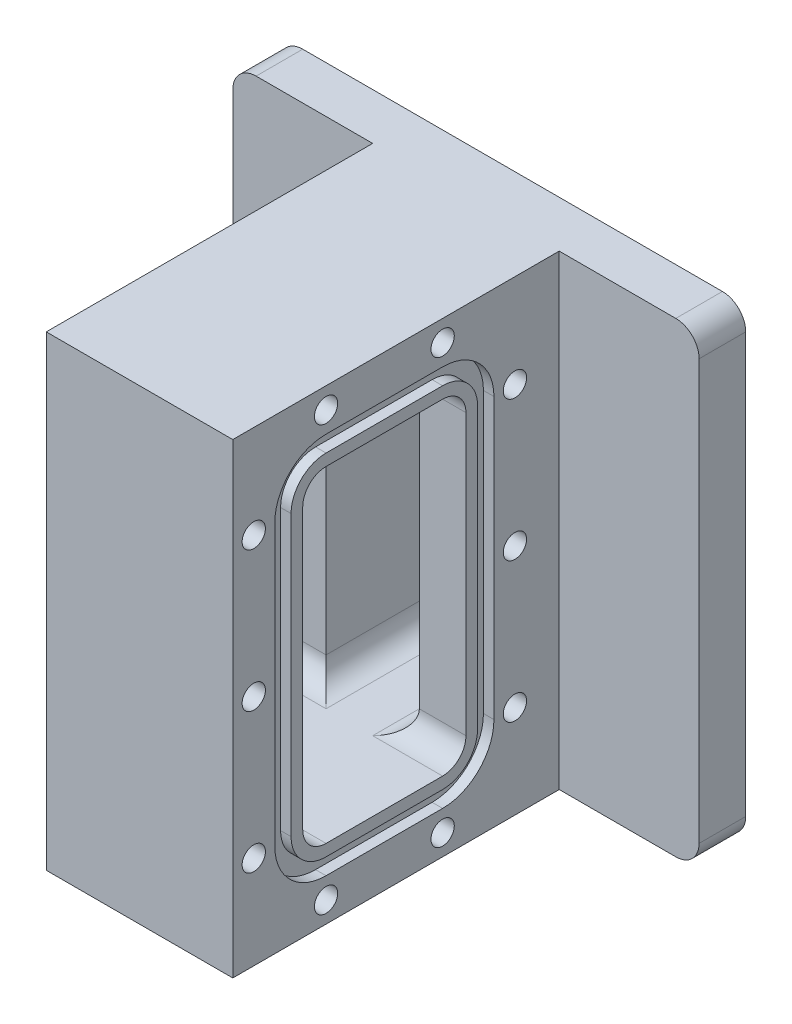
SolidWorks part; units mm, degrees
ref_plane "Front Plane" through (0, 0, 0) normal (0, 0, 1) x (1, 0, 0)
ref_plane "Top Plane" through (0, 0, 0) normal (0, 1, 0) x (1, 0, 0)
ref_plane "Right Plane" through (0, 0, 0) normal (1, 0, 0) x (0, 0, -1)
ref_plane "Plane1" through (99.9998, 0, 0) normal (1, 0, 0) x (0, 0, -1)
sketch "Sketch1" plane through (99.9998, 0, 0) normal (1, 0, 0) x (0, 0, -1)
  line L0 (0, 90.9998) -> (-79.9998, 90.9998)
  line L1 (-79.9998, 90.9998) -> (-79.9998, 0)
  line L2 (-79.9998, 0) -> (0, 0)
  line L3 (0, 0) -> (0, 90.9998)
extrude "Boss-Extrude1" add sketch "Sketch1" against normal blind 67.7499
sketch "Sketch2" plane through (32.2499, 0, 0) normal (-1, 0, 0) x (0, 0, 1)
  line L0 (0, 90.9998) -> (24, 90.9998)
  line L1 (24, 90.9998) -> (24, 9)
  line L2 (24, 9) -> (70.9999, 9)
  line L3 (70.9999, 9) -> (70.9999, 90.9998)
  line L4 (70.9999, 90.9998) -> (79.9998, 90.9998)
  line L5 (79.9998, 90.9998) -> (79.9998, 0)
  line L6 (79.9998, 0) -> (0, 0)
  line L7 (0, 0) -> (0, 90.9998)
extrude "Boss-Extrude2" add sketch "Sketch2" along normal blind 32.2499
sketch "Sketch3" plane through (0, 0, 0) normal (-1, 0, 0) x (0, 0, 1)
  line L0 (70.9999, 9) -> (24, 9)
  line L1 (24, 9) -> (24, 0)
  line L2 (24, 0) -> (79.9998, 0)
  line L3 (79.9998, 0) -> (79.9998, 90.9998)
  line L4 (79.9998, 90.9998) -> (70.9999, 90.9998)
  line L5 (70.9999, 90.9998) -> (70.9999, 9)
extrude "Cut-Extrude1" cut sketch "Sketch3" against normal blind 29.9999
sketch "Sketch4" plane through (0, 0, 24) normal (0, 0, 1) x (1, 0, 0)
  line L0 (29.9999, 0) -> (29.9999, 90.9998)
  line L1 (29.9999, 90.9998) -> (0, 90.9998)
  line L2 (0, 90.9998) -> (0, 0)
  line L3 (0, 0) -> (29.9999, 0)
extrude "Cut-Extrude2" cut sketch "Sketch4" against normal blind 14
sketch "Sketch5" plane through (99.9998, 0, 0) normal (1, 0, 0) x (0, 0, -1)
  line L0 (-10, 0) -> (-10, 90.9998)
  line L1 (-10, 90.9998) -> (-79.9998, 90.9998)
  line L2 (-79.9998, 90.9998) -> (-79.9998, 0)
  line L3 (-79.9998, 0) -> (-10, 0)
extrude "Cut-Extrude3" cut sketch "Sketch5" against normal blind 29.9999
sketch "Sketch6" plane through (32.2499, 0, 0) normal (-1, 0, 0) x (0, 0, 1)
  line L0 (27.4999, 87.4998) -> (67.4999, 87.4998)
  line L1 (67.4999, 87.4998) -> (67.4999, 12.5)
  line L2 (67.4999, 12.5) -> (27.4999, 12.5)
  line L3 (27.4999, 12.5) -> (27.4999, 87.4998)
extrude "Boss-Extrude3" add sketch "Sketch6" along normal blind 2.25
sketch "Sketch7" plane through (0, 0, 0) normal (0, 0, -1) x (-1, 0, 0)
  line L0 (-59.9999, 15) -> (-39.9999, 15)
  line L1 (-39.9999, 15) -> (-39.9999, 84.9998)
  line L2 (-39.9999, 84.9998) -> (-59.9999, 84.9998)
  line L3 (-59.9999, 84.9998) -> (-59.9999, 15)
extrude "Cut-Extrude4" cut sketch "Sketch7" against normal blind 29.9999
sketch "Sketch8" plane through (0, 0, 29.9999) normal (0, 0, -1) x (-1, 0, 0)
  line L0 (-29.9999, 15) -> (-29.9999, 84.9998)
  line L1 (-29.9999, 84.9998) -> (-69.9999, 84.9998)
  line L2 (-69.9999, 84.9998) -> (-69.9999, 15)
  line L3 (-69.9999, 15) -> (-29.9999, 15)
extrude "Cut-Extrude5" cut sketch "Sketch8" against normal blind 34.9999
sketch "Sketch9" plane through (69.9999, 0, 0) normal (1, 0, 0) x (0, 0, -1)
  line L0 (-70.9999, 9) -> (-24, 9)
  line L1 (-24, 9) -> (-24, 90.9998)
  line L2 (-24, 90.9998) -> (-70.9999, 90.9998)
  line L3 (-70.9999, 90.9998) -> (-70.9999, 9)
  line L4 (-67.4999, 87.4998) -> (-27.4999, 87.4998)
  line L5 (-27.4999, 87.4998) -> (-27.4999, 12.5)
  line L6 (-27.4999, 12.5) -> (-67.4999, 12.5)
  line L7 (-67.4999, 12.5) -> (-67.4999, 87.4998)
extrude "Cut-Extrude6" cut sketch "Sketch9" against normal blind 2.25
sketch "Sketch10" plane through (0, 90.9998, 0) normal (0, 1, 0) x (-1, 0, 0)
  line L0 (-29.9999, 10) -> (0, 10)
  line L1 (0, 10) -> (0, 0)
  line L2 (0, 0) -> (-99.9998, 0)
  line L3 (-99.9998, 0) -> (-99.9998, 10)
  line L4 (-99.9998, 10) -> (-69.9999, 10)
  line L5 (-69.9999, 10) -> (-69.9999, 79.9998)
  line L6 (-69.9999, 79.9998) -> (-29.9999, 79.9998)
  line L7 (-29.9999, 79.9998) -> (-29.9999, 10)
extrude "Boss-Extrude4" add sketch "Sketch10" along normal blind 9
hole_wizard "#10 Clearance Hole1" positions "Sketch12" profile "Sketch11" hole size "#10" standard "ANSI Inch"
sketch "Sketch12" plane through (29.9999, 0, 0) normal (-1, 0, 0) x (0, 0, 1)
  point P0 (19.5, 79.9998)
  point P1 (59.9999, 95.4998)
  point P2 (19.5, 49.9999)
  point P3 (34.9999, 4.5)
  point P4 (75.4998, 20)
  point P5 (75.4998, 49.9999)
  point P6 (59.9999, 4.5)
  point P7 (19.5, 20)
  point P8 (75.4998, 79.9998)
  point P9 (34.9999, 95.4998)
sketch "Sketch11" plane through (29.9999, 79.9998, 19.5) normal (0, 1, 0) x (0, 0, 1)
  line L0 (0, 0) -> (0, 7)
  line L1 (0, 7) -> (2.5, 7)
  line L2 (2.5, 7) -> (2.5, 0)
  line L5 (2.5, 0) -> (0, 0)
  line L10 (0, 7) -> (-2.5, 7) construction
  line L11 (0, -6.35) -> (0, 107.95) construction
  dimension "Hole Dia." = 5
  dimension "Hole Depth" = 7
  dimension "Drill Angle" = 180
hole_wizard "#10 Clearance Hole2" positions "Sketch14" profile "Sketch13" hole size "#10" standard "ANSI Inch"
sketch "Sketch14" plane through (69.9999, 0, 0) normal (1, 0, 0) x (0, 0, -1)
  point P0 (-59.9999, 4.5)
  point P1 (-75.4998, 49.9999)
  point P2 (-59.9999, 95.4998)
  point P3 (-19.5, 79.9998)
  point P4 (-19.5, 20)
  point P5 (-34.9999, 4.5)
  point P6 (-19.5, 49.9999)
  point P7 (-34.9999, 95.4998)
  point P8 (-75.4998, 79.9998)
  point P9 (-75.4998, 20)
sketch "Sketch13" plane through (69.9999, 4.5, 59.9999) normal (0, 1, 0) x (0, 0, -1)
  line L0 (0, 0) -> (0, 7)
  line L1 (0, 7) -> (2.5, 7)
  line L2 (2.5, 7) -> (2.5, 0)
  line L5 (2.5, 0) -> (0, 0)
  line L10 (0, 7) -> (-2.5, 7) construction
  line L11 (0, -6.35) -> (0, 107.95) construction
  dimension "Hole Dia." = 5
  dimension "Hole Depth" = 7
  dimension "Drill Angle" = 180
fillet "Fillet1" radius 5 14 edges at (64.9999, 84.9998, 29.9999) (59.9999, 84.9998, 15) (49.9999, 84.9998, 64.9999) (34.9999, 84.9998, 29.9999) (39.9999, 84.9998, 15) (0, 0, 5) (99.9998, 0, 5) (34.9999, 15, 29.9999) (39.9999, 15, 15) (49.9999, 15, 64.9999) (59.9999, 15, 15) (64.9999, 15, 29.9999) (99.9998, 99.9998, 5) (0, 99.9998, 5)
fillet "Fillet2" radius 7.5 8 edges at (68.8749, 12.5, 67.4999) (68.8749, 87.4998, 27.4999) (68.8749, 12.5, 27.4999) (31.1249, 12.5, 27.4999) (68.8749, 87.4998, 67.4999) (31.1249, 12.5, 67.4999) (31.1249, 87.4998, 67.4999) (31.1249, 87.4998, 27.4999)
fillet "Fillet3" radius 11 8 edges at (68.8749, 90.9998, 24) (68.8749, 9, 70.9999) (68.8749, 9, 24) (31.1249, 90.9998, 70.9999) (68.8749, 90.9998, 70.9999) (31.1249, 9, 70.9999) (31.1249, 9, 24) (31.1249, 90.9998, 24)
